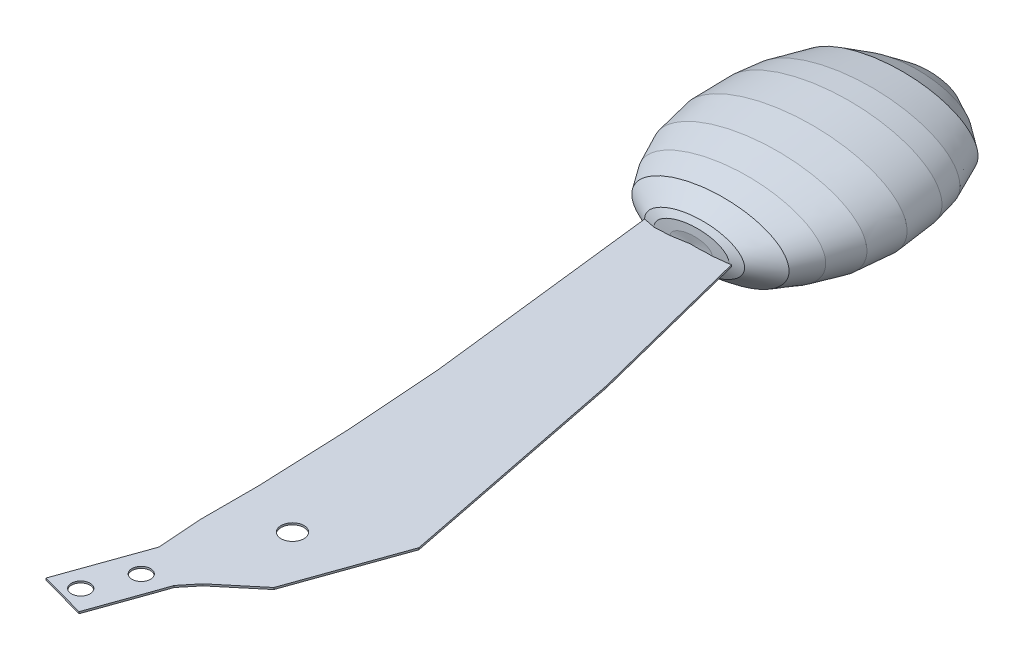
SolidWorks part; units mm, degrees
ref_plane "Front Plane" through (0, 0, 0) normal (0, 0, 1) x (1, 0, 0)
ref_plane "Top Plane" through (0, 0, 0) normal (0, 1, 0) x (1, 0, 0)
ref_plane "Right Plane" through (0, 0, 0) normal (1, 0, 0) x (0, 0, -1)
sketch "Sketch1" plane through (0, 0, 0) normal (0, 1, 0) x (1, 0, 0)
  line L0 (756, -336) -> (756, -1680) construction
  line L1 (242.5547, -1562.5609) -> (294.2017, -1417.4347)
  line L2 (294.2017, -1417.4347) -> (288.6417, -1339.1192)
  line L3 (288.6417, -1339.1192) -> (288.6417, -1238.6533)
  line L4 (288.6417, -1238.6533) -> (282.16, -1078.2319)
  line L5 (282.16, -1078.2319) -> (270.069, -907.9237)
  line L6 (270.069, -907.9237) -> (220.4463, -481.5573)
  line L7 (220.4463, -481.5573) -> (245.2577, -490.3871)
  line L8 (245.2577, -490.3871) -> (285.4009, -496.6225)
  line L9 (285.4009, -496.6225) -> (319.3113, -496.6225)
  line L10 (319.3113, -496.6225) -> (346.0989, -493.5048)
  line L11 (346.0989, -493.5048) -> (365.4482, -485.9722)
  line L12 (365.4482, -485.9722) -> (440.7739, -783.8016)
  line L13 (440.7739, -783.8016) -> (485.0462, -1006.7388)
  line L14 (485.0462, -1006.7388) -> (521.7882, -1191.7565)
  line L15 (521.7882, -1191.7565) -> (455.4099, -1378.2769)
  line L16 (455.4099, -1378.2769) -> (388.0541, -1434.4089)
  line L17 (388.0541, -1434.4089) -> (365.4482, -1462.0488)
  line L18 (365.4482, -1462.0488) -> (355.7736, -1489.9978)
  line L19 (355.7736, -1489.9978) -> (322.1168, -1584.572)
  line L20 (322.1168, -1584.572) -> (242.5547, -1562.5609)
  circle A0 centre (388.0541, -1278.3586) radius 19.9394
  circle A2 centre (288.6417, -1548.0881) radius 16.1765
  circle A3 centre (319.3113, -1473.3261) radius 16.1765
  point P2 (551.0073, -1593.7129)
  point P3 (452.7425, -452.96)
  point P26 (0, 0)
  point P30 (288.6417, -1548.0881)
  point P31 (0, 0)
  point P33 (322.1168, -1473.3261)
  dimension "D1" = 1140.7529
extrude "Boss-Extrude1" add sketch "Sketch1" along normal blind 3.175
scale "Scale1" scale about centroid uniform scaling yes scale factor 0.15586
sketch "Sketch2" plane through (0, 1.8349, 0) normal (0, 1, 0) x (1, 0, 0)
  line L0 (220.4463, -481.5573) -> (187.79, -468.1993)
  line L1 (187.79, -468.1993) -> (162.6946, -435.9338)
  line L2 (162.6946, -435.9338) -> (118.9569, -369.2518)
  line L3 (118.9569, -369.2518) -> (106.0507, -275.3234)
  line L4 (106.0507, -275.3234) -> (106.0507, -148.1695)
  line L5 (106.0507, -148.1695) -> (140.8258, -101.4123)
  line L6 (140.8258, -101.4123) -> (204.1181, -59.898)
  line L7 (204.1181, -59.898) -> (248.4088, -53.8122)
  line L8 (248.4088, -53.8122) -> (308.7692, -53.8122)
  line L9 (308.7692, -53.8122) -> (355.5263, -80.6552)
  line L10 (355.5263, -80.6552) -> (400.4143, -114.04)
  line L11 (400.4143, -114.04) -> (429.9126, -175.0902)
  line L12 (429.9126, -175.0902) -> (442.1517, -218.5783)
  line L13 (442.1517, -218.5783) -> (451.8536, -289.1864)
  line L14 (451.8536, -289.1864) -> (447.0026, -354.2789)
  line L15 (447.0026, -354.2789) -> (429.9126, -408.9916)
  line L16 (429.9126, -408.9916) -> (409.0516, -452.0666)
  line L17 (409.0516, -452.0666) -> (365.4482, -485.9722)
  line L18 (365.4482, -485.9722) -> (346.0989, -493.5048)
  line L19 (346.0989, -493.5048) -> (319.3113, -496.6225)
  line L20 (319.3113, -496.6225) -> (285.4009, -496.6225)
  line L21 (285.4009, -496.6225) -> (245.2577, -490.3871)
  line L22 (245.2577, -490.3871) -> (220.4463, -481.5573)
  line L23 (285.4009, -496.6225) -> (248.4088, -53.8122)
revolve "Revolve1" add sketch "Sketch2" angle 360 about L23
scale "Scale2" bodies to scale 105 scale about centroid uniform scaling yes scale factor 0.15586
move or copy body "Body-Move/Copy1" bodies to move or copy 106 copy no translate (84.6153, 0, 610.2443)
move or copy body "Body-Move/Copy2" bodies to move or copy 107 copy no translate (-2.3696, 0, -1.409)
scale "Scale3" bodies to scale 108 scale about centroid uniform scaling no x scale factor 1 y scale factor 0.5 z scale factor 1
move or copy body "Body-Move/Copy3" bodies to move or copy 109 copy no translate (0, 0, 1.5912)
